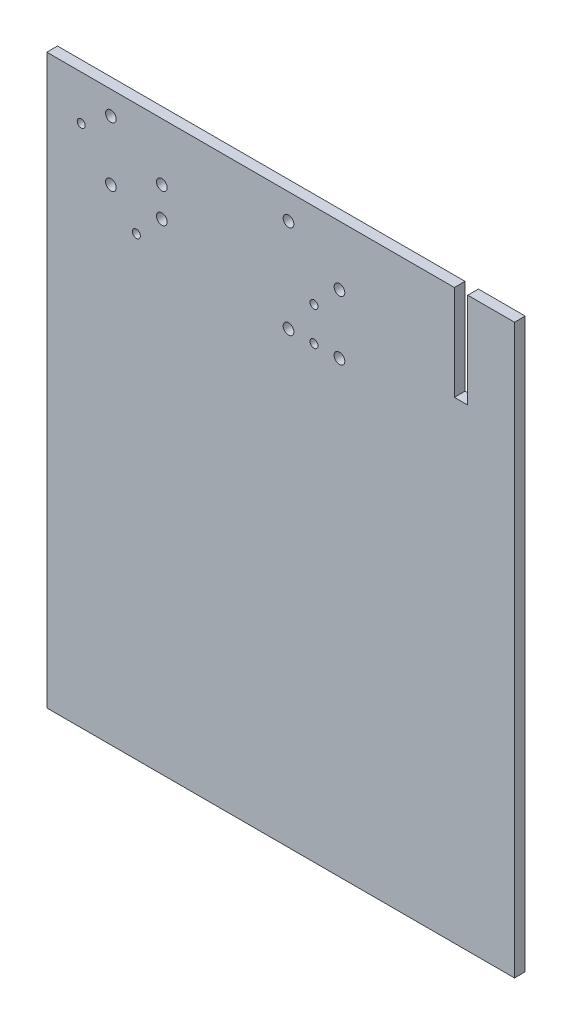
SolidWorks part; units mm, degrees
ref_plane "Front Plane" through (0, 0, 0) normal (0, 0, 1) x (1, 0, 0)
ref_plane "Top Plane" through (0, 0, 0) normal (0, 1, 0) x (1, 0, 0)
ref_plane "Right Plane" through (0, 0, 0) normal (1, 0, 0) x (0, 0, -1)
sketch "Sketch1" plane through (0, 0, 0) normal (0, 0, 1) x (1, 0, 0)
  line L0 (28, 42.5) -> (28, 28.26)
  line L1 (-35, -42.5) -> (35, -42.5)
  line L2 (-35, -42.5) -> (-35, 42.5)
  line L3 (-35, 42.5) -> (26, 42.5)
  line L4 (35, -42.5) -> (35, 42.5)
  line L5 (-35, -42.5) -> (35, 42.5) construction
  line L6 (-35, 42.5) -> (35, -42.5) construction
  line L7 (28, 28.26) -> (26, 28.26)
  line L8 (26, 28.26) -> (26, 42.5)
  line L9 (28, 42.5) -> (35, 42.5)
  point P0 (0, 0)
  dimension "D1" = 70
  dimension "D2" = 85
  dimension "D3" = 63
  dimension "D4" = 2
  dimension "D5" = 14.24
extrude "Boss-Extrude1" add sketch "Sketch1" along normal blind 1.6
sketch "Sketch2" plane through (0, 0, 1.6) normal (0, 0, 1) x (1, 0, 0)
  line L0 (-33.7332, 42.8195) -> (-10.1223, 42.8195) construction
  line L1 (-21.5953, 25.6695) -> (-21.5953, 42.8195) construction
  line L2 (-25.4053, 39.0095) -> (-25.4053, 30.1195) construction
  line L3 (-17.7853, 33.9295) -> (-17.7853, 29.4845) construction
  line L4 (1.178, 24.7194) -> (4.988, 24.7194) construction
  line L5 (4.988, 24.7194) -> (8.798, 24.7194) construction
  line L6 (8.798, 24.7194) -> (8.798, 33.6094) construction
  line L7 (1.178, 24.7194) -> (1.178, 38.6894) construction
  line L8 (-7.3165, 42.4994) -> (16.1596, 42.4994) construction
  line L9 (8.798, 33.6094) -> (8.798, 42.4994) construction
  line L10 (4.988, 24.7194) -> (4.988, 29.7994) construction
  line L11 (1.178, 38.6894) -> (1.178, 42.4994) construction
  line L12 (4.988, 29.7994) -> (4.988, 42.4994) construction
  circle A0 centre (-21.5953, 25.6695) radius 0.6
  circle A1 centre (-17.7853, 29.4845) radius 0.8
  circle A2 centre (-25.4053, 30.1195) radius 0.8
  circle A3 centre (-17.7853, 33.9295) radius 0.8
  circle A4 centre (-25.4053, 39.0095) radius 0.8
  circle A5 centre (-29.8453, 35.8395) radius 0.6
  circle A6 centre (4.988, 24.7194) radius 0.6
  circle A7 centre (8.798, 24.7194) radius 0.8
  circle A8 centre (1.178, 24.7194) radius 0.8
  circle A9 centre (4.988, 29.7994) radius 0.6
  circle A10 centre (8.798, 33.6094) radius 0.8
  circle A11 centre (1.178, 38.6894) radius 0.8
  point P32 (4.988, 24.7194)
  dimension "D10" = 1.2
  dimension "D11" = 1.6
  dimension "D1" = 4.45
  dimension "D2" = 0.635
  dimension "D3" = 12.7
  dimension "D4" = 6.98
  dimension "D5" = 3.81
  dimension "D6" = 8.89
  dimension "D7" = 3.81
  dimension "D8" = 8.25
  dimension "D9" = 3.81
  dimension "D12" = 3.81
  dimension "D13" = 3.81
  dimension "D14" = 12.7
  dimension "D15" = 17.78
  dimension "D16" = 3.81
  dimension "D17" = 8.89
extrude "Cut-Extrude1" cut sketch "Sketch2" against normal through all
